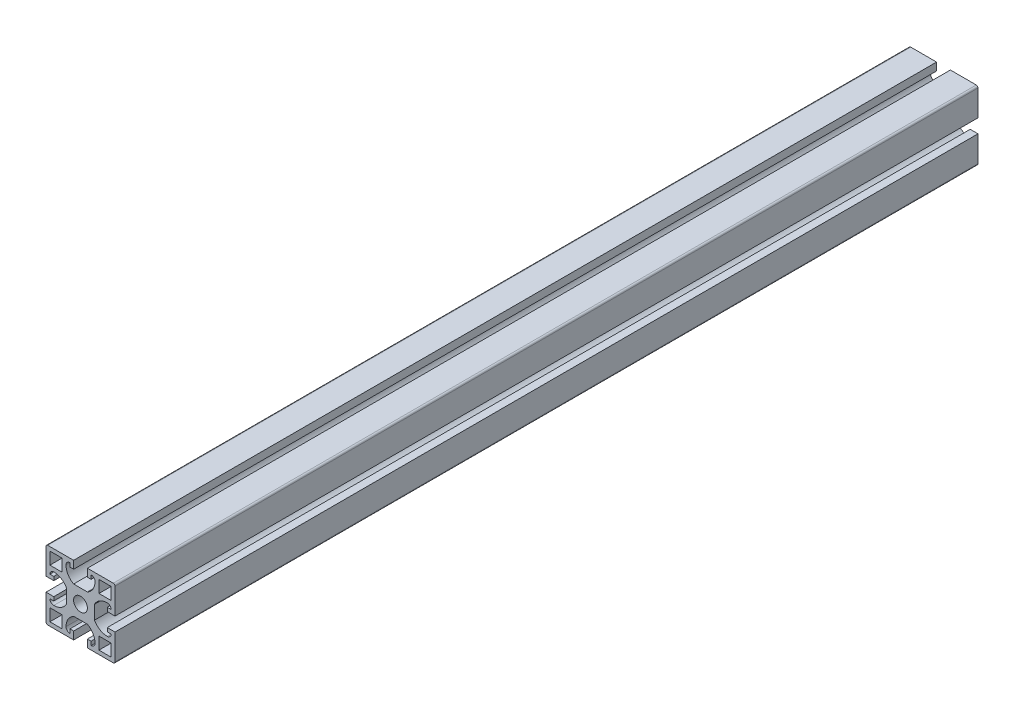
SolidWorks part; units mm, degrees
material "3.0255 (EN-AW 1350A)"
ref_plane "Płaszczyzna przednia" through (0, 0, 0) normal (0, 0, 1) x (1, 0, 0)
ref_plane "Płaszczyzna górna" through (0, 0, 0) normal (0, 1, 0) x (1, 0, 0)
ref_plane "Płaszczyzna prawa" through (0, 0, 0) normal (1, 0, 0) x (0, 0, -1)
sketch "Szkic1" plane through (0, 0, 0) normal (0, 0, 1) x (1, 0, 0)
  line L0 (4, 20) -> (4, 15.5)
  line L1 (4, 15.5) -> (6.1661, 15.5)
  line L13 (6.1661, 15.5) -> (6.1661, 17.75)
  line L35 (0, 0) -> (40.9069, 40.9069) construction
  line L103 (4, 8.0952) -> (-4, 8.0952)
  line L104 (-10.6789, 10.6789) -> (-10.6789, 17.75)
  line L127 (-10.6789, 17.75) -> (-17.75, 17.75)
  line L128 (-4, 20) -> (-19, 20)
  line L129 (4, 20) -> (19, 20)
  line L131 (10.6789, 10.6789) -> (10.6789, 17.75)
  line L132 (10.6789, 17.75) -> (17.75, 17.75)
  line L134 (-6.1661, 15.5) -> (-6.1661, 17.75)
  line L135 (-4, 15.5) -> (-6.1661, 15.5)
  line L136 (-4, 20) -> (-4, 15.5)
  line L137 (0, 35.4784) -> (0, -28.3735) construction
  line L138 (-42.5787, 0) -> (50.8455, 0) construction
  line L139 (10.6789, 10.6789) -> (17.75, 10.6789)
  line L140 (17.75, 10.6789) -> (17.75, 17.75)
  line L141 (20, 4) -> (20, 19)
  line L142 (15.5, 6.1661) -> (17.75, 6.1661)
  line L143 (15.5, 4) -> (15.5, 6.1661)
  line L144 (20, -4) -> (15.5, -4)
  line L145 (15.5, -4) -> (15.5, -6.1661)
  line L146 (15.5, -6.1661) -> (17.75, -6.1661)
  line L147 (20, -4) -> (20, -19)
  line L148 (17.75, -10.6789) -> (17.75, -17.75)
  line L149 (10.6789, -10.6789) -> (17.75, -10.6789)
  line L150 (8.0952, 4) -> (8.0952, -4)
  line L151 (20, 4) -> (15.5, 4)
  line L152 (-39.6979, 39.6979) -> (27.244, -27.244) construction
  line L153 (4, -20) -> (19, -20)
  line L154 (-20, 4) -> (-20, 19)
  line L155 (-17.75, 10.6789) -> (-17.75, 17.75)
  line L156 (-4, -20) -> (-4, -15.5)
  line L157 (-4, -8.0952) -> (4, -8.0952)
  line L158 (10.6789, -10.6789) -> (10.6789, -17.75)
  line L159 (10.6789, -17.75) -> (17.75, -17.75)
  line L160 (6.1661, -15.5) -> (6.1661, -17.75)
  line L161 (4, -15.5) -> (6.1661, -15.5)
  line L162 (4, -20) -> (4, -15.5)
  line L163 (-4, -15.5) -> (-6.1661, -15.5)
  line L164 (-6.1661, -15.5) -> (-6.1661, -17.75)
  line L165 (-4, -20) -> (-19, -20)
  line L166 (-10.6789, -17.75) -> (-17.75, -17.75)
  line L167 (-10.6789, -10.6789) -> (-10.6789, -17.75)
  line L168 (-20, 4) -> (-15.5, 4)
  line L169 (-15.5, 4) -> (-15.5, 6.1661)
  line L170 (-15.5, 6.1661) -> (-17.75, 6.1661)
  line L171 (-17.75, -10.6789) -> (-17.75, -17.75)
  line L172 (-10.6789, -10.6789) -> (-17.75, -10.6789)
  line L173 (-20, -4) -> (-20, -19)
  line L174 (-10.6789, 10.6789) -> (-17.75, 10.6789)
  line L175 (-8.0952, -4) -> (-8.0952, 4)
  line L176 (-15.5, -6.1661) -> (-17.75, -6.1661)
  line L177 (-15.5, -4) -> (-15.5, -6.1661)
  line L178 (-20, -4) -> (-15.5, -4)
  arc A57 (6.1661, 17.75) -> (8.4161, 15.5) centre (6.1661, 15.5) cw
  arc A58 (8.4161, 15.5) -> (4, 8.0952) centre (0, 15.5) cw
  arc A59 (-6.1661, 17.75) -> (-8.4161, 15.5) centre (-6.1661, 15.5) ccw
  arc A60 (-8.4161, 15.5) -> (-4, 8.0952) centre (0, 15.5) ccw
  arc A61 (15.5, 8.4161) -> (8.0952, 4) centre (15.5, 0) ccw
  arc A62 (17.75, 6.1661) -> (15.5, 8.4161) centre (15.5, 6.1661) ccw
  arc A63 (15.5, -8.4161) -> (8.0952, -4) centre (15.5, 0) cw
  arc A64 (17.75, -6.1661) -> (15.5, -8.4161) centre (15.5, -6.1661) cw
  arc A65 (6.1661, -17.75) -> (8.4161, -15.5) centre (6.1661, -15.5) ccw
  arc A66 (8.4161, -15.5) -> (4, -8.0952) centre (0, -15.5) ccw
  arc A67 (-6.1661, -17.75) -> (-8.4161, -15.5) centre (-6.1661, -15.5) cw
  arc A68 (-8.4161, -15.5) -> (-4, -8.0952) centre (0, -15.5) cw
  arc A69 (-15.5, 8.4161) -> (-8.0952, 4) centre (-15.5, 0) cw
  arc A70 (-17.75, 6.1661) -> (-15.5, 8.4161) centre (-15.5, 6.1661) cw
  arc A71 (-15.5, -8.4161) -> (-8.0952, -4) centre (-15.5, 0) ccw
  arc A72 (-17.75, -6.1661) -> (-15.5, -8.4161) centre (-15.5, -6.1661) ccw
  arc A73 (-19, -20) -> (-20, -19) centre (-19, -19) cw
  arc A74 (20, -19) -> (19, -20) centre (19, -19) cw
  arc A75 (19, 20) -> (20, 19) centre (19, 19) cw
  arc A76 (-19, 20) -> (-20, 19) centre (-19, 19) ccw
  circle A77 centre (0, 0) radius 4
  point P9 (4, 17.75)
  point P18 (0, 8.0952)
  point P48 (8.0952, 0)
  point P86 (0, -8.0952)
  point P87 (-8.0952, 0)
  point P91 (-20, -20)
  point P94 (20, -20)
  point P97 (20, 20)
  point P100 (-20, 20)
  dimension "D4" = 8
  dimension "D5" = 1
  dimension "D2" = 10
  dimension "D3" = 40
  dimension "D6" = 8
  dimension "D1" = 4.5
  dimension "D7" = 8.0952
extrude "Dodanie-wyciągnięcie1" add sketch "Szkic1" along normal blind 500 contours L128 A76 L154 L168 L169 L170 A70 A69 L175 A71 A72 L176 L177 L178 L173 A73 L165 L156 L163 L164 A67 A68 L157 A66 A65 L160 L161 L162 L153 A74 L147 L144 L145 L146 A64 A63 L150 A61 A62 L142 L143 L151 L141 A75 L129 L0 L1 L13 A57 A58 L103
